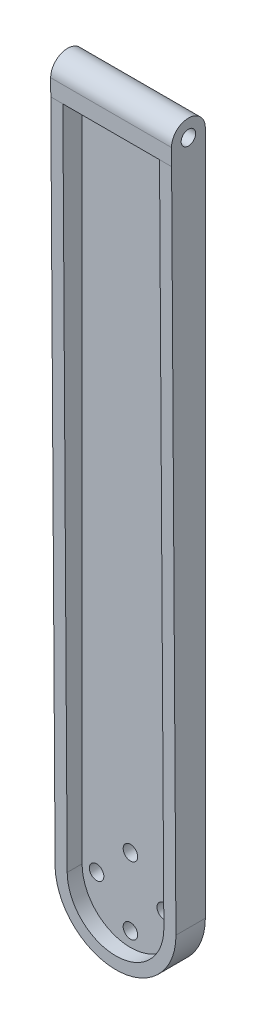
SolidWorks part; units mm, degrees
ref_plane "前视基准面" through (0, 0, 0) normal (0, 0, 1) x (1, 0, 0)
ref_plane "上视基准面" through (0, 0, 0) normal (0, 1, 0) x (1, 0, 0)
ref_plane "右视基准面" through (0, 0, 0) normal (1, 0, 0) x (0, 0, -1)
sketch "草图1" plane through (0, 0, 0) normal (0, 0, 1) x (1, 0, 0)
  line L2 (-12.5, -62.827) -> (-12.5, 75.327)
  line L3 (-12.5, 75.327) -> (12.5, 75.327)
  line L4 (12.5, -62.827) -> (12.5, 75.327)
  arc A0 (-12.5, -62.827) -> (12.5, -62.827) centre (0, -62.827) ccw
  circle A1 centre (7, -62.827) radius 1.5
  circle A2 centre (0, -69.827) radius 1.5
  circle A3 centre (-7, -62.827) radius 1.5
  circle A4 centre (0, -55.827) radius 1.5
  point P0 (0, 0)
  point P22 (0, -62.827)
  dimension "D1" = 4
extrude "凸台-拉伸1" add sketch "草图1" along normal blind 3
sketch "草图3" plane through (0, 0, 3) normal (0, 0, 1) x (1, 0, 0)
  line L0 (10, -62.827) -> (10, 72.827)
  line L2 (-10, 72.827) -> (-10, -62.827)
  line L3 (12.5, -62.827) -> (12.5, 75.327)
  line L4 (12.5, 75.327) -> (-12.5, 75.327)
  line L5 (-12.5, 75.327) -> (-12.5, -62.827)
  line L6 (12.5, -62.827) -> (12.5, 75.327)
  line L7 (12.5, 75.327) -> (10, 75.327)
  line L8 (-12.5, 75.327) -> (-12.5, -62.827)
  line L9 (10, 72.827) -> (-10, 72.827) construction
  line L10 (-10, 72.827) -> (-10, 75.327)
  line L11 (10, 72.827) -> (10, 75.327)
  line L12 (-10, 75.327) -> (-12.5, 75.327)
  line L14 (12.5, 75.327) -> (-12.5, 75.327) construction
  arc A0 (-10, -62.827) -> (10, -62.827) centre (0, -62.827) ccw
  arc A1 (-12.5, -62.827) -> (12.5, -62.827) centre (0, -62.827) ccw
  arc A2 (-12.5, -62.827) -> (12.5, -62.827) centre (0, -62.827) ccw
  dimension "D1" = 0
  dimension "D2" = 2.5
extrude "凸台-拉伸3" add sketch "草图3" along normal blind 25
sketch "草图4" plane through (12.5, 0, 0) normal (1, 0, 0) x (0, 0, -1)
  line L0 (0, 75.327) -> (0, 78.7911)
  line L1 (0, 75.327) -> (-3, 75.327)
  line L2 (-28, 75.327) -> (0, 75.327) construction
  line L3 (-3, 75.327) -> (-3.5, 75.327)
  line L4 (0, -62.827) -> (0, -75.3287)
  line L5 (0, -75.3287) -> (-6, -75.3287)
  line L6 (-6, -75.3287) -> (-6.9999, 78.7684)
  line L7 (0, 75.327) -> (-6.9776, 75.327)
  arc A1 (0, 78.7911) -> (-6.9999, 78.7684) centre (-3.5, 78.7911) ccw
  circle A2 centre (-3.5, 78.7911) radius 1.5
  line M8 (0, 75.327) -> (-28, 75.327)
extrude "凸台-拉伸5" add sketch "草图4" against normal blind 25 contours L0 A1 L6 A2 M8
sketch "草图5" plane through (12.5, 0, 0) normal (1, 0, 0) x (0, 0, -1)
  line L2 (-6, -75.327) -> (-6.9776, 75.327)
  line L3 (-6.9776, 75.327) -> (-6.9999, 78.7684) construction
  line L4 (-6.9776, 75.327) -> (-30.364, 75.327)
  line L5 (-30.364, 75.327) -> (-30.364, -75.327)
  line L6 (-30.364, -75.327) -> (-6, -75.327)
extrude "切除-拉伸1" cut sketch "草图5" against normal blind 25
